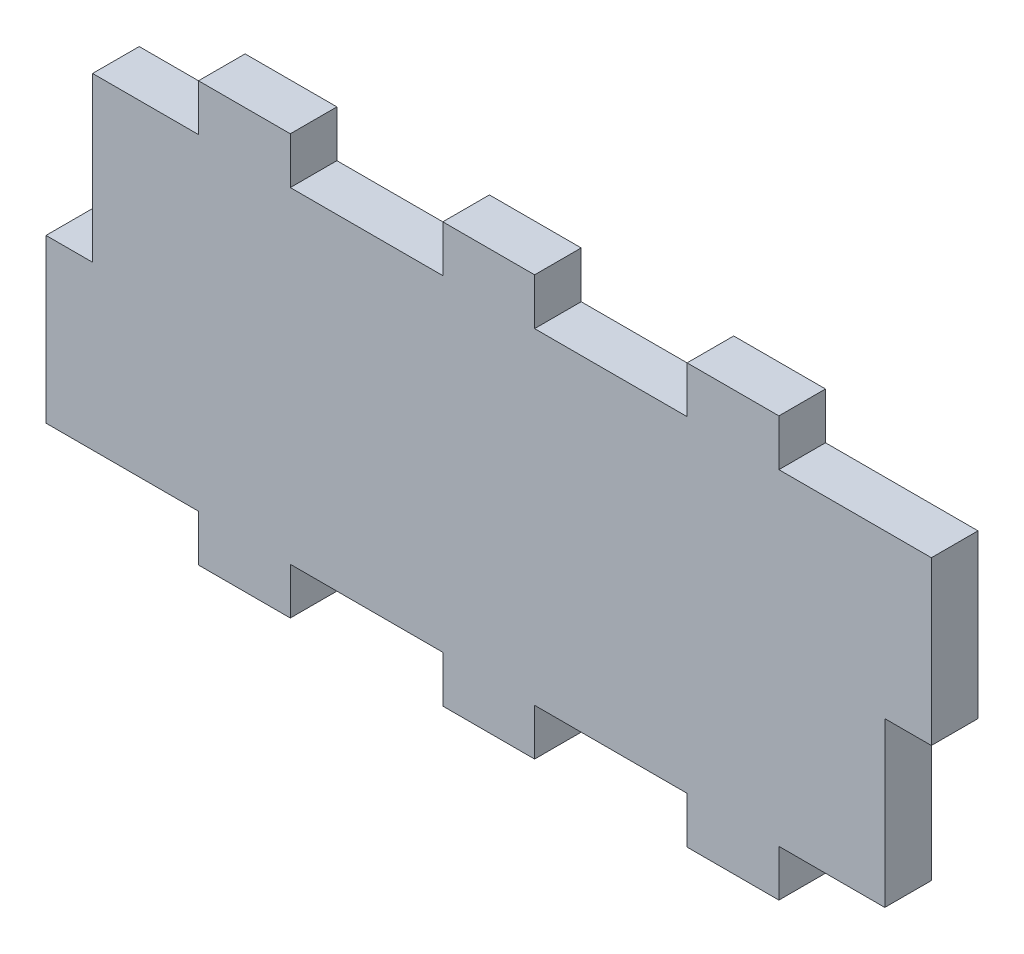
SolidWorks part; units mm, degrees
ref_plane "Front Plane" through (0, 0, 0) normal (0, 0, 1) x (1, 0, 0)
ref_plane "Top Plane" through (0, 0, 0) normal (0, 1, 0) x (1, 0, 0)
ref_plane "Right Plane" through (0, 0, 0) normal (1, 0, 0) x (0, 0, -1)
sketch "Sketch2" plane through (0, 0, 0) normal (0, 0, 1) x (1, 0, 0)
  line L0 (-31.1375, 22.5) -> (-31.1375, 17.5)
  line L1 (-42.5, -17.5) -> (42.5, -17.5)
  line L2 (-42.5, -17.5) -> (-42.5, 17.5)
  line L3 (-42.5, 17.5) -> (42.5, 17.5)
  line L4 (42.5, -17.5) -> (42.5, 17.5)
  line L5 (-42.5, -17.5) -> (42.5, 17.5) construction
  line L6 (-42.5, 17.5) -> (42.5, -17.5) construction
  line L7 (-42.5, -17.5) -> (-47.5, -17.5)
  line L8 (-42.5, -17.5) -> (-42.5, -0.05)
  line L9 (-42.5, -0.05) -> (-47.5, -0.05)
  line L10 (-47.5, -17.5) -> (-47.5, -0.05)
  line L11 (-31.1375, -17.5) -> (-21.2875, -17.5)
  line L12 (-31.1375, -17.5) -> (-31.1375, -22.5)
  line L13 (-31.1375, -22.5) -> (-21.2875, -22.5)
  line L14 (-21.2875, -17.5) -> (-21.2875, -22.5)
  line L15 (-4.925, -17.5) -> (4.925, -17.5)
  line L16 (-4.925, -17.5) -> (-4.925, -22.5)
  line L17 (-4.925, -22.5) -> (4.925, -22.5)
  line L18 (4.925, -17.5) -> (4.925, -22.5)
  line L19 (21.2875, -17.5) -> (31.1375, -17.5)
  line L20 (21.2875, -17.5) -> (21.2875, -22.5)
  line L21 (21.2875, -22.5) -> (31.1375, -22.5)
  line L22 (31.1375, -17.5) -> (31.1375, -22.5)
  line L23 (42.5, 17.5) -> (47.5, 17.5)
  line L24 (42.5, 17.5) -> (42.5, 0.05)
  line L25 (42.5, 0.05) -> (47.5, 0.05)
  line L26 (47.5, 17.5) -> (47.5, 0.05)
  line L27 (-31.1375, 22.5) -> (-21.2875, 22.5)
  line L28 (-21.2875, 22.5) -> (-21.2875, 17.5)
  line L29 (-31.1375, 17.5) -> (-21.2875, 17.5)
  line L30 (-4.925, 22.5) -> (-4.925, 17.5)
  line L31 (-4.925, 22.5) -> (4.925, 22.5)
  line L32 (4.925, 22.5) -> (4.925, 17.5)
  line L33 (-4.925, 17.5) -> (4.925, 17.5)
  line L34 (21.2875, 22.5) -> (21.2875, 17.5)
  line L35 (21.2875, 22.5) -> (31.1375, 22.5)
  line L36 (31.1375, 22.5) -> (31.1375, 17.5)
  line L37 (21.2875, 17.5) -> (31.1375, 17.5)
  line L38 (21.2875, -20) -> (4.925, -20) construction
  line L39 (-4.925, -20) -> (-21.2875, -20) construction
  line L42 (31.1375, -20) -> (47.5, -20) construction
  line L43 (47.5, -20) -> (47.5, 0.05) construction
  line L44 (-31.1375, -20) -> (-47.5, -20) construction
  line L45 (-47.5, -20) -> (-47.5, -17.5) construction
  point P0 (0, 0)
  dimension "D1" = 35
  dimension "D2" = 85
  dimension "D3" = 17.45
  dimension "D4" = 5
  dimension "D5" = 5
  dimension "D6" = 5
  dimension "D7" = 5
  dimension "D8" = 9.85
  dimension "D9" = 9.85
  dimension "D10" = 9.85
  dimension "D13" = 5
  dimension "D14" = 17.45
  dimension "D16" = 2
extrude "Boss-Extrude1" add sketch "Sketch2" along normal blind 5 contours L1 L4 L3 L2 | L10 L7 L2 L9 | L28 L27 L0 L3 | L32 L31 L30 L3 | L36 L35 L34 L3 | L26 L23 L4 L25 | L22 L1 L20 L21 | L18 L1 L16 L17 | L14 L1 L12 L13
